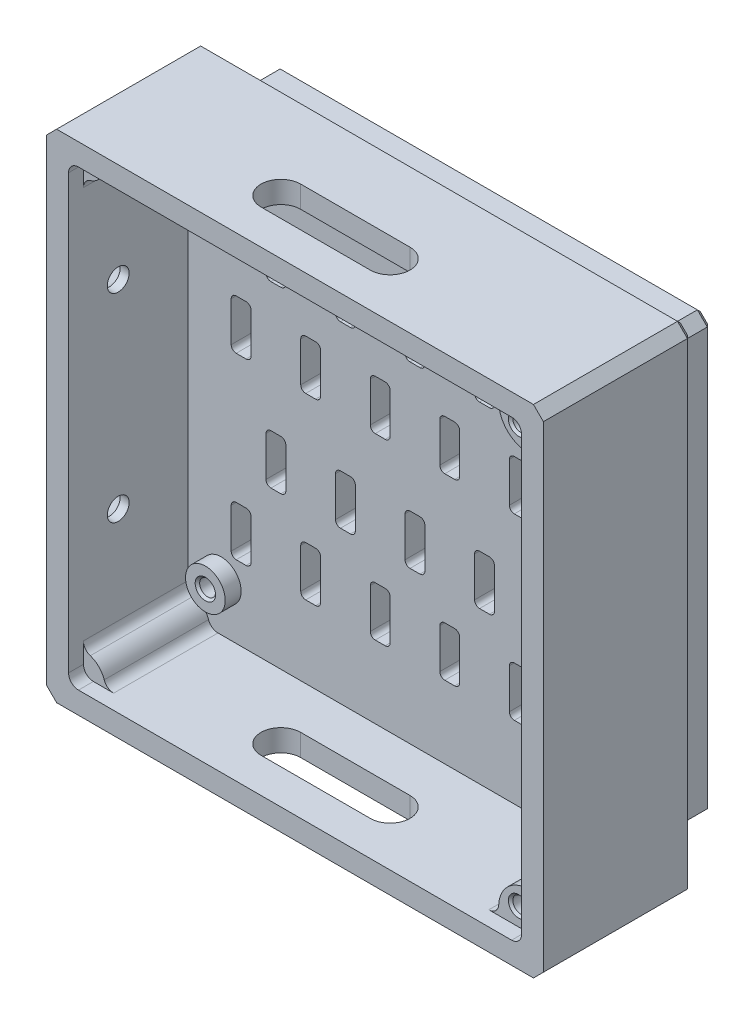
SolidWorks part; units mm, degrees
ref_plane "前视基准面" through (0, 0, 0) normal (0, 0, 1) x (1, 0, 0)
ref_plane "上视基准面" through (0, 0, 0) normal (0, 1, 0) x (1, 0, 0)
ref_plane "右视基准面" through (0, 0, 0) normal (1, 0, 0) x (0, 0, -1)
sketch "草图1" plane through (0, 0, 0) normal (0, 0, 1) x (1, 0, 0)
  line L1 (-25, 25) -> (25, 25)
  line L2 (-25, 25) -> (-25, -25)
  line L3 (-25, -25) -> (25, -25)
  line L4 (25, 25) -> (25, -25)
  line L5 (-25, 25) -> (25, -25) construction
  line L6 (-25, -25) -> (25, 25) construction
  point P0 (0, 0)
  dimension "D1" = 50
  dimension "D2" = 50
extrude "凸台-拉伸1" add sketch "草图1" along normal blind 20
sketch "草图2" plane through (0, 0, 20) normal (0, 0, 1) x (1, 0, 0)
  line L0 (25, -25) -> (25, 25) construction
  line L1 (-22.8, 22.8) -> (22.8, 22.8)
  line L2 (-22.8, 22.8) -> (-22.8, -22.8)
  line L3 (-22.8, -22.8) -> (22.8, -22.8)
  line L4 (22.8, 22.8) -> (22.8, -22.8)
  line L5 (-22.8, 22.8) -> (22.8, -22.8) construction
  line L6 (-22.8, -22.8) -> (22.8, 22.8) construction
  line L7 (-25, -25) -> (25, -25) construction
  point P0 (0, 0)
  dimension "D1" = 2.2
  dimension "D2" = 2.2
extrude "切除-拉伸1" cut sketch "草图2" against normal blind 12
sketch "草图3" plane through (0, 0, 8) normal (0, 0, 1) x (1, 0, 0)
  circle A0 centre (-19.427, 18) radius 2
  circle A1 centre (16.5731, 18) radius 2
  circle A2 centre (16.5731, -18) radius 2
  circle A3 centre (-19.427, -18) radius 2
  dimension "D1" = 4
  dimension "D2" = 4
  dimension "D3" = 4
  dimension "D4" = 4
extrude "凸台-拉伸2" add sketch "草图3" along normal blind 1.6
hole_wizard "M2 螺纹孔1" positions "草图6" profile "草图7" tap size "M2" standard "GB"
sketch "草图6" plane through (0, 0, 9.6) normal (0, 0, 1) x (1, 0, 0)
  point P0 (-19.427, 18)
  point P3 (16.5731, 18)
  point P6 (16.5731, -18)
  point P9 (-19.427, -18)
sketch "草图7" plane through (-19.427, 18, 9.6) normal (1, 0, 0) x (0, -1, 0)
  line L0 (0, 0) -> (0, 6.4807)
  line L1 (0, 6.4807) -> (0.8, 6)
  line L2 (0.8, 6) -> (0.8, 0.225)
  line L3 (0.8, 0.225) -> (1.025, 0)
  line L5 (1.025, 0) -> (0, 0)
  line L6 (-0.8, 0.225) -> (-1.025, 0) construction
  line L10 (0, 6.4807) -> (-0.8, 6) construction
  line L11 (0, -6.35) -> (0, 107.95) construction
  dimension "螺纹孔钻头直径" = 1.6
  dimension "螺纹孔钻头深度" = 6
  dimension "近端锥形沉头孔直径" = 2.05
  dimension "近端锥形沉头孔角度" = 90
  dimension "导头角度" = 118
cosmetic thread "孔螺蚊线5" parameters "D1"=4, "D2"=2
cosmetic thread "孔螺蚊线6" parameters "D1"=4, "D2"=2
cosmetic thread "孔螺蚊线7" parameters "D1"=4, "D2"=2
cosmetic thread "孔螺蚊线8" parameters "D1"=4, "D2"=2
sketch "草图8" plane through (0, 0, 8) normal (0, 0, 1) x (1, 0, 0)
  line L3 (-22.8, 22.8) -> (-22.8, -22.8) construction
  line L11 (22.8, 22.8) -> (-22.8, 22.8) construction
  line L12 (25, 25) -> (-25, 25) construction
  line L14 (25, -25) -> (25, 25) construction
  line L15 (-25, -25) -> (25, -25) construction
  circle A5 centre (-22.8, 22.8) radius 2.2
  circle A6 centre (22, 22) radius 3
  circle A7 centre (-22.8, -22.8) radius 2.2
  circle A8 centre (22, -22) radius 3
  dimension "D1" = 6
  dimension "D2" = 6
extrude "凸台-拉伸7" add sketch "草图8" along normal offset from surface (10.5 mm away) 1.5 up to face at (0, 0, 20)
fillet "圆角1" radius 1 12 edges at (22.8, -22.8, 19.25) (-22.8, -22.8, 19.25) (-22.8, 22.8, 19.25) (22.8, 22.8, 19.25) (22.8, 19.1086, 13.25) (19.1086, 22.8, 13.25) (22.8, -19.1086, 13.25) (19.1086, -22.8, 13.25) (-20.6, -22.8, 13.25) (-22.8, -20.6, 13.25) (-20.6, 22.8, 13.25) (-22.8, 20.6, 13.25)
hole_wizard "M2 螺纹孔4" positions "草图14" profile "草图15" tap size "M2" standard "GB"
sketch "草图14" plane through (0, 0, 18.5) normal (0, 0, 1) x (1, 0, 0)
  line L0 (22.8, -21.8) -> (22.8, 21.8) construction
  line L1 (21.8, 22.8) -> (-21.8, 22.8) construction
  line L3 (-21.8, -22.8) -> (21.8, -22.8) construction
  point P0 (21, 21)
  point P2 (21, -21)
  dimension "D1" = 1.8
  dimension "D2" = 1.8
  dimension "D3" = 1.8
sketch "草图15" plane through (21, 21, 18.5) normal (1, 0, 0) x (0, -1, 0)
  line L0 (0, 0) -> (0, 6.4807)
  line L1 (0, 6.4807) -> (0.8, 6)
  line L2 (0.8, 6) -> (0.8, 0.225)
  line L3 (0.8, 0.225) -> (1.025, 0)
  line L5 (1.025, 0) -> (0, 0)
  line L6 (-0.8, 0.225) -> (-1.025, 0) construction
  line L10 (0, 6.4807) -> (-0.8, 6) construction
  line L11 (0, -6.35) -> (0, 107.95) construction
  dimension "螺纹孔钻头直径" = 1.6
  dimension "螺纹孔钻头深度" = 6
  dimension "近端锥形沉头孔直径" = 2.05
  dimension "近端锥形沉头孔角度" = 90
  dimension "导头角度" = 118
cosmetic thread "孔螺蚊线11" parameters "D1"=4, "D2"=2
cosmetic thread "孔螺蚊线12" parameters "D1"=4, "D2"=2
sketch "草图16" plane through (-25, 0, 0) normal (-1, 0, 0) x (0, 0, 1)
  line L0 (15, 10) -> (15, -10) construction
  line L1 (20, 25) -> (20, -25) construction
  circle A0 centre (15, 10) radius 1.1
  circle A1 centre (15, -10) radius 1.1
  point P5 (15, 0)
  dimension "D1" = 2.2
  dimension "D2" = 2.2
  dimension "D3" = 20
  dimension "D4" = 5
extrude "切除-拉伸2" cut sketch "草图16" against normal blind 11.5
chamfer "倒角1" distance 0.9 distance2 1.3 2 edges at (-25, 8.9, 15) (-25, -11.1, 15)
sketch "草图17" plane through (0, 25, 0) normal (0, 1, 0) x (1, 0, 0)
  line L0 (-6.927, -12.5) -> (4.073, -12.5) construction
  line L1 (4.073, -16.5) -> (-6.927, -16.5) construction
  line L2 (-6.927, -12.5) -> (4.073, -12.5)
  line L3 (4.073, -16.5) -> (-6.927, -16.5)
  arc A0 (-6.927, -12.5) -> (-6.927, -16.5) centre (-6.927, -14.5) ccw construction
  arc A1 (4.073, -16.5) -> (4.073, -12.5) centre (4.073, -14.5) ccw construction
  arc A2 (-6.927, -12.5) -> (-6.927, -16.5) centre (-6.927, -14.5) ccw
  arc A3 (4.073, -16.5) -> (4.073, -12.5) centre (4.073, -14.5) ccw
extrude "切除-拉伸3" cut sketch "草图17" against normal blind 3
sketch "草图18" plane through (0, 0, 0) normal (0, 0, -1) x (-1, 0, 0)
  line L0 (-22, 22) -> (-22, -22)
  line L1 (-22, -22) -> (22, -22)
  line L2 (22, -22) -> (22, 22)
  line L3 (22, 22) -> (-22, 22)
  line L4 (-25, 25) -> (-25, -25)
  line L5 (-25, -25) -> (25, -25)
  line L6 (25, -25) -> (25, 25)
  line L7 (25, 25) -> (-25, 25)
  line L8 (-25, 25) -> (-25, -25)
  line L9 (-25, -25) -> (25, -25)
  line L10 (25, -25) -> (25, 25)
  line L11 (25, 25) -> (-25, 25)
  dimension "D1" = 0
  dimension "D2" = 3
extrude "切除-拉伸4" cut sketch "草图18" against normal blind 5
chamfer "倒角2" distance 1 angle 45 8 edges at (-22, -22, 2.5) (22, -22, 2.5) (22, 22, 2.5) (-22, 22, 2.5) (-25, 25, 12.5) (-25, -25, 12.5) (25, -25, 12.5) (25, 25, 12.5)
sketch "草图19" plane through (0, 0, 0) normal (0, 0, -1) x (-1, 0, 0)
  line L0 (-11.5731, 10.5) -> (-11.5731, 15.5) construction
  line L1 (-15.0731, 15.5) -> (-13.0731, 15.5)
  line L2 (-15.0731, 15.5) -> (-15.0731, 10.5)
  line L3 (-15.0731, 10.5) -> (-13.0731, 10.5)
  line L4 (-13.0731, 15.5) -> (-13.0731, 10.5)
  line L6 (-14.4731, 12.4) -> (-13.6731, 12.4) construction
  line L7 (-13.6731, -4.4) -> (-14.4731, -4.4) construction
  line L8 (-15.0731, -2.5) -> (-13.0731, -2.5)
  line L9 (-15.0731, -2.5) -> (-15.0731, -7.5)
  line L10 (-15.0731, -7.5) -> (-13.0731, -7.5)
  line L11 (-13.0731, -2.5) -> (-13.0731, -7.5)
  line L12 (-11.5731, -7.5) -> (-11.5731, -2.5) construction
  point P6 (-11.5731, 13)
  point P7 (-13.0731, 13)
  point P10 (-14.0731, 12.4)
  point P11 (-14.0731, 15.5)
  point P18 (-14.0731, -4.4)
  point P19 (-14.0731, -2.5)
  point P22 (-11.5731, -5)
  point P23 (-13.0731, -5)
  dimension "D1" = 5
  dimension "D2" = 2
  dimension "D3" = 5
  dimension "D4" = 2
extrude "切除-拉伸5" cut sketch "草图19" against normal through all
fillet "圆角2" radius 0.5 8 edges at (15.0731, -7.5, 4) (13.0731, -7.5, 4) (13.0731, -2.5, 4) (15.0731, -2.5, 4) (15.0731, 10.5, 4) (13.0731, 10.5, 4) (15.0731, 15.5, 4) (13.0731, 15.5, 4)
pattern_linear "阵列(线性)1" count 5 spacing 7 along (-1, 0, 0) of "切除-拉伸5", "圆角2"
sketch "草图20" plane through (0, 0, 0) normal (0, 0, -1) x (-1, 0, 0)
  line L1 (-11.5731, 7.5) -> (-9.5731, 7.5)
  line L2 (-11.5731, 7.5) -> (-11.5731, 2.5)
  line L3 (-11.5731, 2.5) -> (-9.5731, 2.5)
  line L4 (-9.5731, 7.5) -> (-9.5731, 2.5)
  line L5 (-11.5731, -10.5) -> (-9.5731, -10.5)
  line L6 (-11.5731, -10.5) -> (-11.5731, -15.5)
  line L7 (-11.5731, -15.5) -> (-9.5731, -15.5)
  line L8 (-9.5731, -10.5) -> (-9.5731, -15.5)
  line L9 (-8.0731, 7.5) -> (-13.0731, 7.5) construction
  line L10 (-8.0731, -10.5) -> (-13.0731, -10.5) construction
  line L11 (-13.0731, -10.5) -> (-13.0731, -15.5) construction
  line L12 (-13.0731, 6.3) -> (-13.0731, 3.7) construction
  point P14 (-10.5731, 7.5)
  point P15 (-10.5731, 7.5)
  point P18 (-10.5731, -10.5)
  point P19 (-10.5731, -10.5)
  point P22 (-13.0731, -13)
  point P23 (-11.5731, -13)
  point P26 (-13.0731, 5)
  point P27 (-11.5731, 5)
  dimension "D1" = 2
  dimension "D2" = 5
  dimension "D3" = 2
  dimension "D4" = 5
extrude "切除-拉伸6" cut sketch "草图20" against normal through all
fillet "圆角3" radius 0.5 8 edges at (9.5731, -10.5, 4) (11.5731, -10.5, 4) (9.5731, -15.5, 4) (11.5731, -15.5, 4) (9.5731, 2.5, 4) (11.5731, 2.5, 4) (11.5731, 7.5, 4) (9.5731, 7.5, 4)
pattern_linear "阵列(线性)2" count 5 spacing 7 along (-1, 0, 0) of "切除-拉伸6", "圆角3"
sketch "草图21" plane through (25, 0, 0) normal (1, 0, 0) x (0, 0, -1)
  arc A4 (-13.7499, 3.0459) -> (-13.7499, -3.1539) centre (-13.7499, -0.054) ccw
  arc A5 (-13.7499, -3.1539) -> (-13.7499, 3.0459) centre (-13.7499, -0.054) ccw
  arc A6 (-13.7499, 3.0459) -> (-13.7499, -3.1539) centre (-13.7499, -0.054) ccw
  arc A7 (-13.7499, -3.1539) -> (-13.7499, 3.0459) centre (-13.7499, -0.054) ccw
  dimension "D1" = 0.1
extrude "切除-拉伸8" [suppressed] cut sketch "草图21" against normal blind 3
chamfer "倒角3" distance 0.5 angle 45 16 edges at (-21.5, 21.5, 0) (-22, 0, 0) (-21.5, -21.5, 0) (0, -22, 0) (21.5, -21.5, 0) (0, 22, 0) (21.5, 21.5, 0) (22, 0, 0) (24.5, 24.5, 5) (0, 25, 5) (-24.5, 24.5, 5) (-25, 0, 5) (-24.5, -24.5, 5) (0, -25, 5) (24.5, -24.5, 5) (25, 0, 5)
sketch "草图22" plane through (0, -25, 0) normal (0, -1, 0) x (1, 0, 0)
  line L2 (-4.937, 12.5) -> (4.363, 12.5)
  line L3 (4.363, 16.5) -> (-4.937, 16.5)
  line L4 (-4.937, 12.5) -> (4.363, 12.5)
  line L5 (4.363, 16.5) -> (-4.937, 16.5)
  arc A2 (4.363, 12.5) -> (4.363, 16.5) centre (4.363, 14.5) ccw
  arc A3 (-4.937, 16.5) -> (-4.937, 12.5) centre (-4.937, 14.5) ccw
  arc A4 (4.363, 12.5) -> (4.363, 16.5) centre (4.363, 14.5) ccw
  arc A5 (-4.937, 16.5) -> (-4.937, 12.5) centre (-4.937, 14.5) ccw
  dimension "D1" = 0
extrude "切除-拉伸9" [suppressed] cut sketch "草图22" against normal blind 10
chamfer "倒角4" [suppressed] distance 0.2 angle 45
sketch "草图23" plane through (22.8, 0, 0) normal (-1, 0, 0) x (0, 0, 1)
  circle A0 centre (13.8769, 10.741) radius 0.8 construction
  circle A1 centre (13.8769, 10.741) radius 0.8 construction
  circle A2 centre (13.8769, -10.849) radius 0.8 construction
  circle A3 centre (13.8769, -10.849) radius 0.8 construction
  circle A4 centre (13.8769, 10.741) radius 1.1
  circle A5 centre (13.8769, -10.849) radius 1.1
  dimension "D1" = 2.2
  dimension "D2" = 2.2
extrude "切除-拉伸10" [suppressed] cut sketch "草图23" against normal blind 10
chamfer "倒角5" [suppressed] distance 1.2 distance2 0.9
sketch "草图24" plane through (0, -25, 0) normal (0, -1, 0) x (1, 0, 0)
  line L0 (-6.927, 16.5) -> (4.073, 16.5) construction
  line L1 (4.073, 12.5) -> (-6.927, 12.5) construction
  line L2 (-6.927, 16.5) -> (4.073, 16.5)
  line L3 (4.073, 12.5) -> (-6.927, 12.5)
  arc A0 (4.073, 12.5) -> (4.073, 16.5) centre (4.073, 14.5) ccw construction
  arc A1 (-6.927, 16.5) -> (-6.927, 12.5) centre (-6.927, 14.5) ccw construction
  arc A2 (4.073, 12.5) -> (4.073, 16.5) centre (4.073, 14.5) ccw
  arc A3 (-6.927, 16.5) -> (-6.927, 12.5) centre (-6.927, 14.5) ccw
extrude "切除-拉伸11" cut sketch "草图24" against normal blind 10
